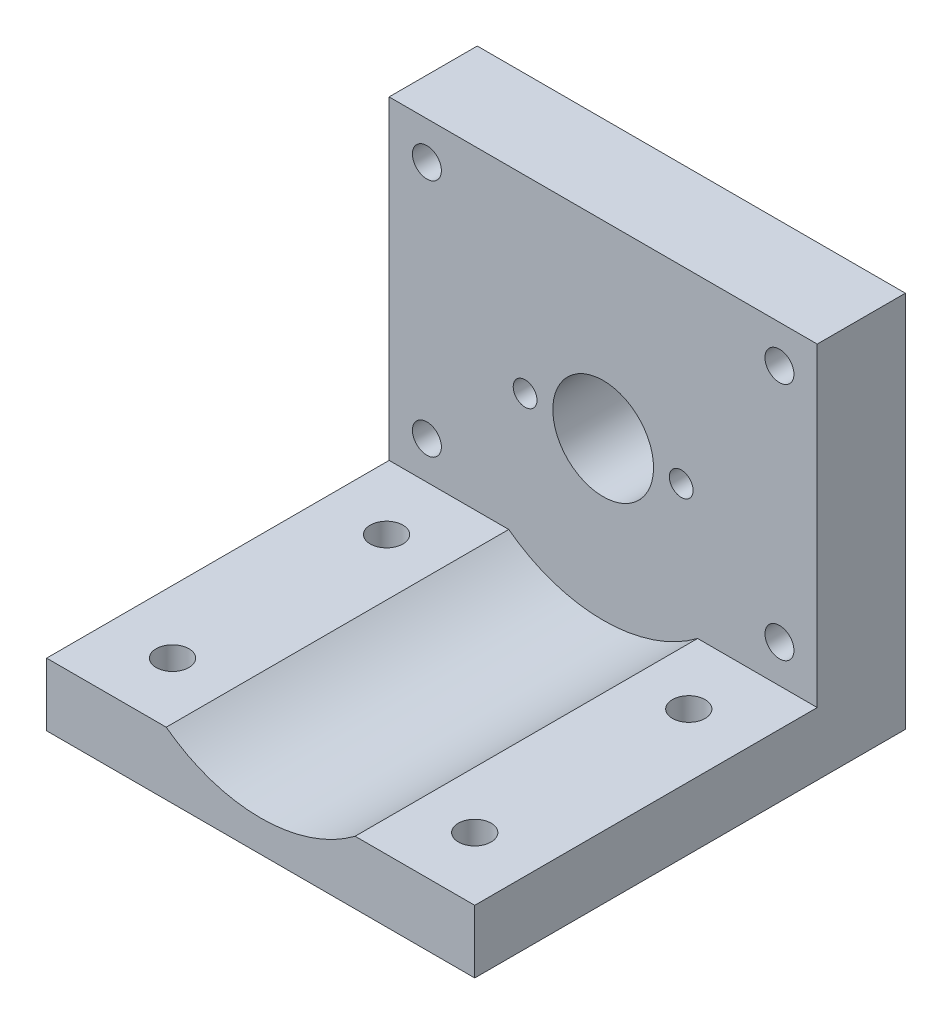
SolidWorks part; units mm, degrees
material "ABS"
ref_plane "Front Plane" through (0, 0, 0) normal (0, 0, 1) x (1, 0, 0)
ref_plane "Top Plane" through (0, 0, 0) normal (0, 1, 0) x (1, 0, 0)
ref_plane "Right Plane" through (0, 0, 0) normal (1, 0, 0) x (0, 0, -1)
sketch "Sketch2" plane through (0, 0, 0) normal (0, 0, 1) x (1, 0, 0)
  line L1 (-21.59, -19.05) -> (21.59, -19.05)
  line L2 (-21.59, -19.05) -> (-21.59, 19.05)
  line L3 (-21.59, 19.05) -> (21.59, 19.05)
  line L4 (21.59, -19.05) -> (21.59, 19.05)
  circle A0 centre (0, 0) radius 5.08
  circle A1 centre (-17.78, 15.24) radius 1.4605
  circle A2 centre (17.78, 15.24) radius 1.4605
  circle A3 centre (17.78, -8.89) radius 1.4605
  circle A4 centre (-17.78, -8.89) radius 1.4605
  point P7 (7.874, 0)
  point P9 (-7.874, 0)
  dimension "D3" = 10.16
  dimension "D6" = 2.921
  dimension "D1" = 43.18
  dimension "D2" = 38.1
  dimension "D4" = 19.05
  dimension "D5" = 21.59
  dimension "D7" = 17.78
  dimension "D8" = 27.94
  dimension "D9" = 3.81
  dimension "D10" = 17.78
  dimension "D11" = 7.874
  dimension "D12" = 7.874
extrude "Boss-Extrude1" add sketch "Sketch2" along normal blind 8.89
sketch "Sketch3" plane through (0, 0, 0) normal (0, 0, 1) x (1, 0, 0)
  point P0 (-7.874, 0)
  point P1 (7.874, 0)
  dimension "D1" = 7.874
  dimension "D2" = 7.874
hole_wizard "CSK for M2 Flat Head Machine Screw4" positions "Sketch3" profile "Sketch7" countersink size "M2" standard "ANSI Metric" end condition through all
sketch "Sketch7" plane through (-7.874, 0, 0) normal (1, 0, 0) x (0, 1, 0)
  line L0 (0, 0) -> (0, 8.89)
  line L1 (0, 8.89) -> (1.2, 8.89)
  line L2 (1.2, 8.89) -> (1.2, 1)
  line L3 (1.2, 1) -> (2.2, 0)
  line L5 (2.2, 0) -> (0, 0)
  line L6 (-1.2, 1) -> (-2.2, 0) construction
  line L11 (0, -6.35) -> (0, 107.95) construction
  dimension "Thru Hole Dia." = 2.4
  dimension "Thru Hole Depth" = 8.89
  dimension "Near C'Sink Dia." = 4.4
  dimension "Near C'Sink Angle" = 90
sketch "Sketch13" plane through (0, 0, 8.89) normal (0, 0, 1) x (1, 0, 0)
  line L0 (-21.59, -12.7) -> (-21.59, -19.05)
  line L1 (-21.59, -19.05) -> (21.59, -19.05)
  line L2 (21.59, -19.05) -> (21.59, -12.7)
  line L5 (-21.59, -12.7) -> (-9.525, -12.7)
  line L7 (21.59, -12.7) -> (9.525, -12.7)
  arc A0 (9.525, -12.7) -> (-9.525, -12.7) centre (0, 0) cw
  dimension "D1" = 15.875
  dimension "D2" = 6.35
  dimension "D3" = 6.35
extrude "Boss-Extrude4" add sketch "Sketch13" along normal blind 34.544
sketch "Sketch17" plane through (0, 0, 0) normal (0, 1, 0) x (1, 0, 0)
  circle A0 centre (-15.24, -15.494) radius 1.651
  circle A1 centre (15.24, -15.494) radius 1.651
  circle A2 centre (-15.24, -37.084) radius 1.651
  circle A3 centre (15.24, -37.084) radius 1.651
  dimension "D1" = 3.302
  dimension "D2" = 30.48
  dimension "D3" = 21.59
  dimension "D4" = 6.35
  dimension "D5" = 6.35
extrude "Cut-Extrude1" cut sketch "Sketch17" against normal blind 34.544
sketch "Sketch18" plane through (0, 0, 0) normal (0, 0, -1) x (-1, 0, 0)
  text T0 "Evan Hou" font "Century Gothic" height in points 12
extrude "Cut-Extrude2" cut sketch "Sketch18" against normal blind 1.27
